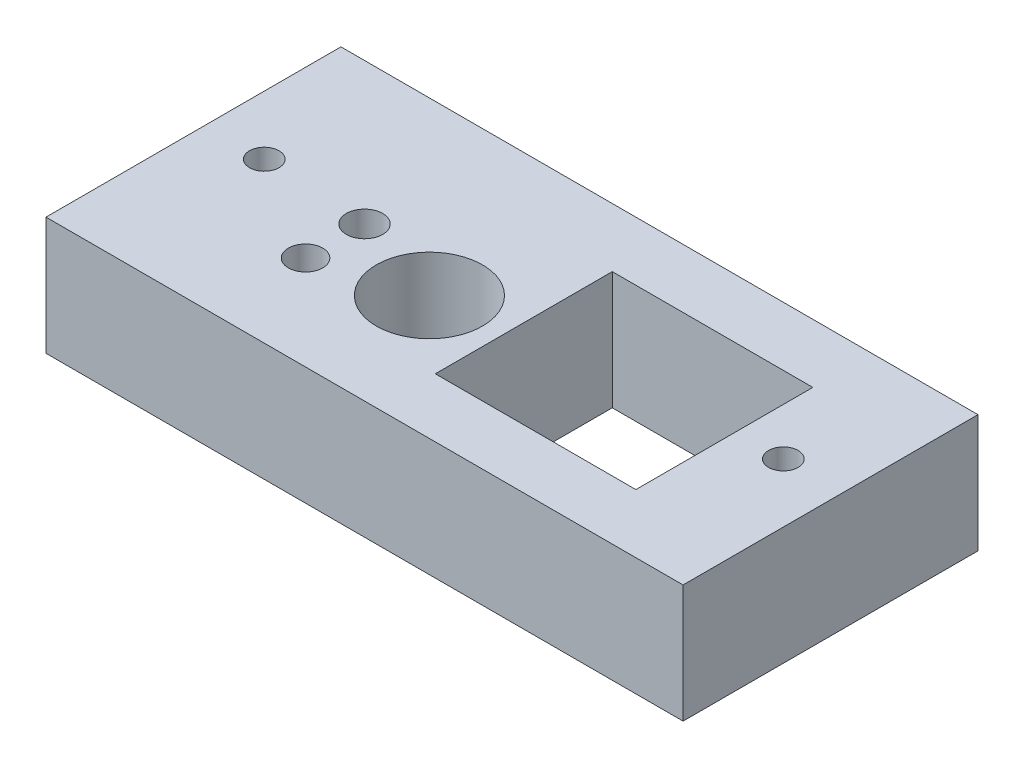
SolidWorks part; units mm, degrees
ref_plane "Front Plane" through (0, 0, 0) normal (0, 0, 1) x (1, 0, 0)
ref_plane "Top Plane" through (0, 0, 0) normal (0, 1, 0) x (1, 0, 0)
ref_plane "Right Plane" through (0, 0, 0) normal (1, 0, 0) x (0, 0, -1)
sketch "Sketch1" plane through (0, 0, 0) normal (0, 1, 0) x (1, 0, 0)
  line L1 (0, 0) -> (54, 0)
  line L2 (0, 0) -> (0, 25)
  line L3 (0, 25) -> (54, 25)
  line L4 (54, 0) -> (54, 25)
  dimension "D1" = 54
  dimension "D2" = 25
extrude "Boss-Extrude1" add sketch "Sketch1" along normal blind 10
sketch "Sketch2" plane through (0, 10, 0) normal (0, 1, 0) x (1, 0, 0)
  line L0 (54, 25) -> (0, 25) construction
  line L1 (28, 20) -> (45, 20)
  line L2 (28, 20) -> (28, 5)
  line L3 (28, 5) -> (45, 5)
  line L4 (45, 20) -> (45, 5)
  line L5 (0, 0) -> (54, 0) construction
  line L6 (2, 25) -> (2, 0) construction
  line L7 (52, 25) -> (52, 0) construction
  line L8 (0, 25) -> (0, 0) construction
  line L9 (54, 0) -> (54, 25) construction
  line L10 (14, 25) -> (14, 0) construction
  circle A0 centre (49, 13.5) radius 1.25
  circle A1 centre (5, 13.5) radius 1.25
  circle A2 centre (22, 10.5) radius 4.5
  circle A3 centre (14, 13) radius 1.5417
  circle A4 centre (14, 8) radius 1.4573
  dimension "D11" = 2.5
  dimension "D12" = 2.5
  dimension "D13" = 9
  dimension "D1" = 5
  dimension "D2" = 5
  dimension "D3" = 2
  dimension "D4" = 2
  dimension "D5" = 17
  dimension "D6" = 7
  dimension "D7" = 13.5
  dimension "D8" = 5
  dimension "D9" = 5
  dimension "D10" = 13.5
  dimension "D14" = 32
  dimension "D15" = 10.5
  dimension "D16" = 40
  dimension "D17" = 13
  dimension "D18" = 8
extrude "Cut-Extrude1" cut sketch "Sketch2" against normal blind 10
